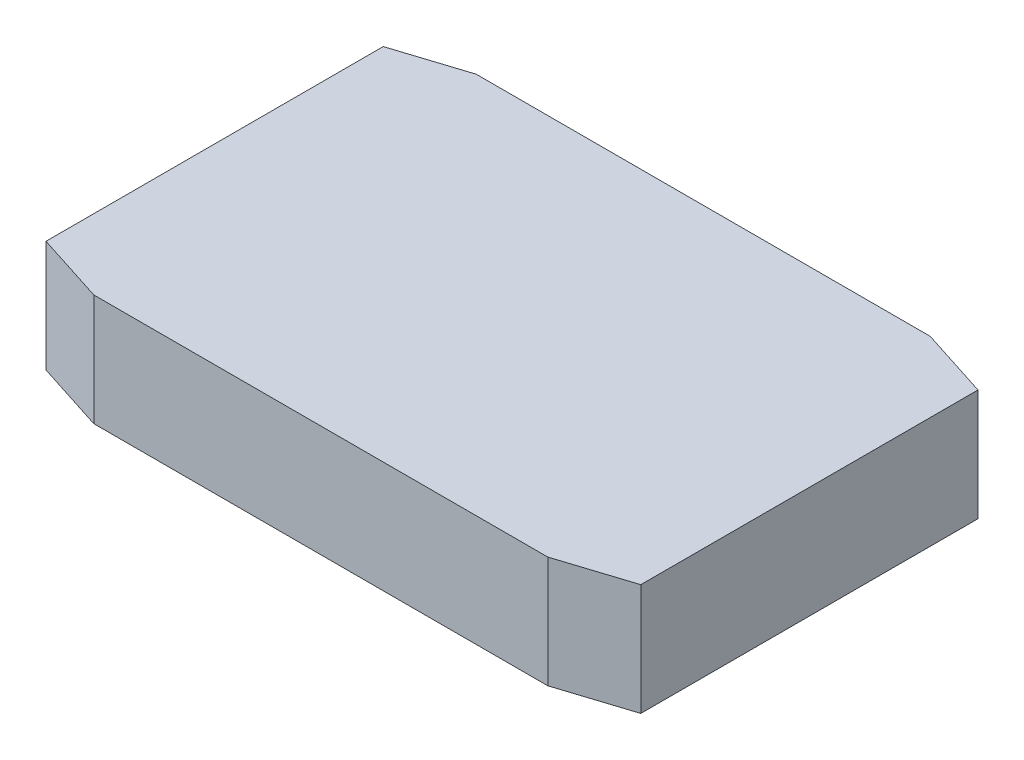
SolidWorks part; units mm, degrees
ref_plane "Front Plane" through (0, 0, 0) normal (0, 0, 1) x (1, 0, 0)
ref_plane "Top Plane" through (0, 0, 0) normal (0, 1, 0) x (1, 0, 0)
ref_plane "Right Plane" through (0, 0, 0) normal (1, 0, 0) x (0, 0, -1)
sketch "Sketch1" plane through (0, 0, 0) normal (0, 1, 0) x (1, 0, 0)
  line L1 (0, 0) -> (224, 0)
  line L2 (0, 0) -> (0, 144)
  line L3 (0, 144) -> (224, 144)
  line L4 (224, 0) -> (224, 144)
  dimension "D1" = 224
  dimension "D2" = 144
extrude "Boss-Extrude1" add sketch "Sketch1" along normal blind 42
sketch "Sketch2" plane through (0, 0, 0) normal (0, -1, 0) x (1, 0, 0)
  line L0 (0, 0) -> (224, 0) construction
  line L1 (24.5, -10.25) -> (199.5, -10.25)
  line L2 (24.5, -10.25) -> (24.5, -21.25)
  line L3 (24.5, -21.25) -> (199.5, -21.25)
  line L4 (199.5, -10.25) -> (199.5, -21.25)
  line L5 (0, -144) -> (0, 0) construction
  line L6 (24.5, -15.75) -> (0, -15.75) construction
  line L7 (199.5, -15.75) -> (224, -15.75) construction
  line L8 (224, 0) -> (224, -144) construction
  line L9 (0, -72) -> (224, -72) construction
  line L10 (24.5, -122.75) -> (199.5, -122.75)
  line L11 (199.5, -133.75) -> (199.5, -122.75)
  line L12 (24.5, -133.75) -> (199.5, -133.75)
  line L13 (24.5, -133.75) -> (24.5, -122.75)
  dimension "D1" = 10.25
  dimension "D2" = 11
  dimension "D3" = 24.5
extrude "Boss-Extrude2" add sketch "Sketch2" along normal blind 4.5 contours L13 L12 L11 L10 | L2 L3 L4 L1
ref_plane "Plane1" through (0, 0, -72) normal (0, 0, -1) x (-1, 0, 0)
ref_plane "Plane2" through (112, 0, 0) normal (1, 0, 0) x (0, 0, -1)
ref_plane "Plane3" through (0, 0, -72) normal (0, 0, -1) x (-1, 0, 0)
ref_plane "Plane4" through (0, 21, 0) normal (0, 1, 0) x (1, 0, 0)
ref_plane "Clearance" through (30, 0, 0) normal (-1, 0, 0) x (0, 0, 1)
ref_plane "Clearance1" through (194, 0, 0) normal (1, 0, 0) x (0, 0, -1)
chamfer "Chamfer1" distance 8.5 distance2 26.5 2 edges at (0, 21, 0) (224, 21, -144)
chamfer "Chamfer2" distance 26.5 distance2 8.5 2 edges at (0, 21, -144) (224, 21, 0)
